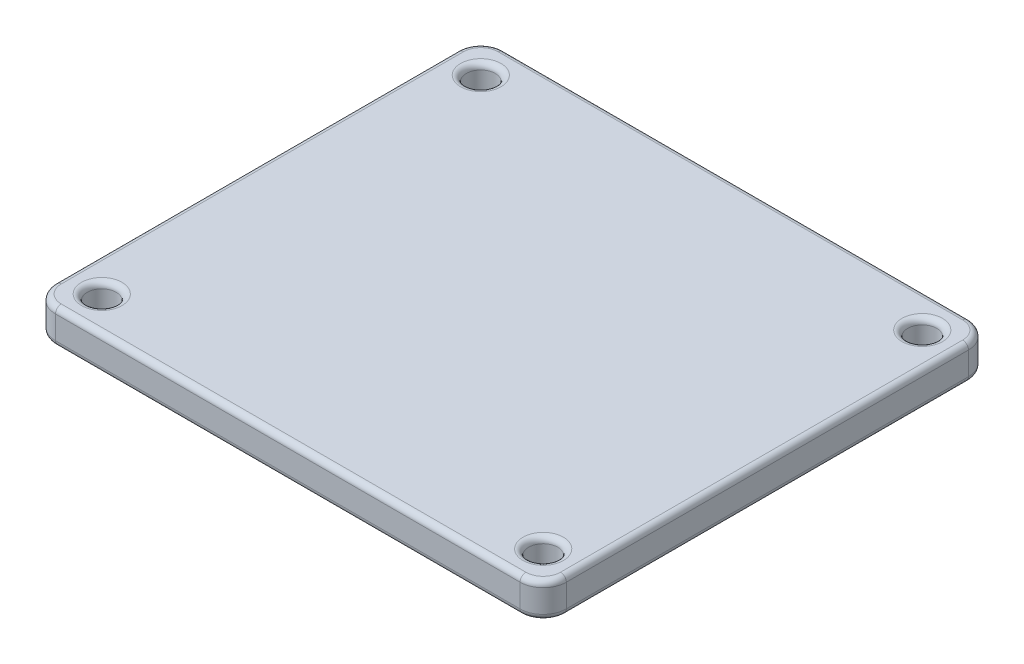
SolidWorks part; units mm, degrees
ref_plane "Front Plane" through (0, 0, 0) normal (0, 0, 1) x (1, 0, 0)
ref_plane "Top Plane" through (0, 0, 0) normal (0, 1, 0) x (1, 0, 0)
ref_plane "Right Plane" through (0, 0, 0) normal (1, 0, 0) x (0, 0, -1)
sketch "Sketch2" plane through (0, 0, 0) normal (0, 1, 0) x (1, 0, 0)
  line L0 (0, 0) -> (0, 50000) construction
  line L1 (-20.1, 19.4) -> (20.1, 19.4)
  line L2 (-22.1, 17.4) -> (-22.1, -17.4)
  line L3 (-20.1, -19.4) -> (20.1, -19.4)
  line L4 (22.1, 17.4) -> (22.1, -17.4)
  line L5 (-22.1, 19.4) -> (22.1, -19.4) construction
  line L6 (-22.1, -19.4) -> (22.1, 19.4) construction
  line L7 (0, 0) -> (50000, 0) construction
  circle A0 centre (-19.1, 16.4) radius 1.25
  circle A1 centre (19.1, 16.4) radius 1.25
  circle A2 centre (19.1, -16.4) radius 1.25
  circle A3 centre (-19.1, -16.4) radius 1.25
  arc A4 (20.1, 19.4) -> (22.1, 17.4) centre (20.1, 17.4) cw
  arc A5 (20.1, -19.4) -> (22.1, -17.4) centre (20.1, -17.4) ccw
  arc A6 (-22.1, -17.4) -> (-20.1, -19.4) centre (-20.1, -17.4) ccw
  arc A7 (-20.1, 19.4) -> (-22.1, 17.4) centre (-20.1, 17.4) ccw
  point P0 (0, 0)
  dimension "D3" = 2.5
  dimension "D6" = 2
  dimension "D1" = 44.2
  dimension "D2" = 38.8
  dimension "D4" = 3
  dimension "D5" = 3
extrude "Boss-Extrude2" add sketch "Sketch2" along normal blind 3
fillet "Fillet3" radius 0.5 24 edges at (-19.1, 0, 15.15) (19.1, 0, -17.65) (0, 0, -19.4) (-21.5142, 0, -18.8142) (-22.1, 0, 0) (-21.5142, 0, 18.8142) (0, 0, 19.4) (21.5142, 0, 18.8142) (22.1, 0, 0) (21.5142, 0, -18.8142) (-19.1, 0, -15.15) (19.1, 0, 17.65) (-19.1, 3, 15.15) (19.1, 3, 17.65) (19.1, 3, -17.65) (-19.1, 3, -15.15) (22.1, 3, 0) (21.5142, 3, 18.8142) (0, 3, 19.4) (-21.5142, 3, 18.8142) (-22.1, 3, 0) (-21.5142, 3, -18.8142) (0, 3, -19.4) (21.5142, 3, -18.8142)
